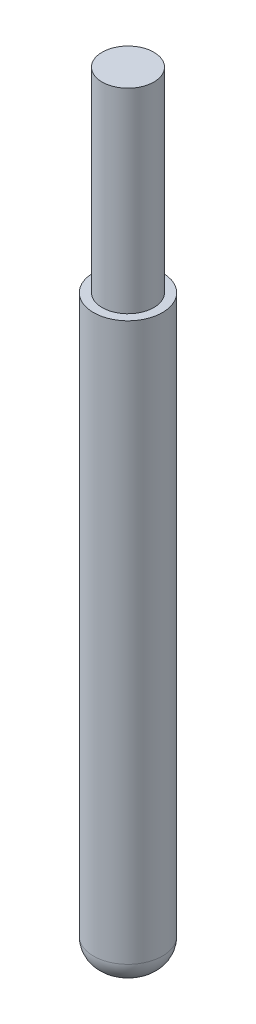
SolidWorks part; units mm, degrees
ref_plane "Front Plane" through (0, 0, 0) normal (0, 0, 1) x (1, 0, 0)
ref_plane "Top Plane" through (0, 0, 0) normal (0, 1, 0) x (1, 0, 0)
ref_plane "Right Plane" through (0, 0, 0) normal (1, 0, 0) x (0, 0, -1)
sketch "Sketch1" plane through (0, 0, 0) normal (0, 1, 0) x (1, 0, 0)
  circle A0 centre (0, 0) radius 3
  dimension "D1" = 6
extrude "Boss-Extrude1" add sketch "Sketch1" along normal blind 50.5
fillet "Fillet1" radius 2 1 edges at (0, 0, 3)
sketch "Sketch2" plane through (0, 50.5, 0) normal (0, 1, 0) x (1, 0, 0)
  circle A0 centre (0, 0) radius 2.25
  dimension "D1" = 4.5
extrude "Boss-Extrude2" add sketch "Sketch2" along normal blind 17
